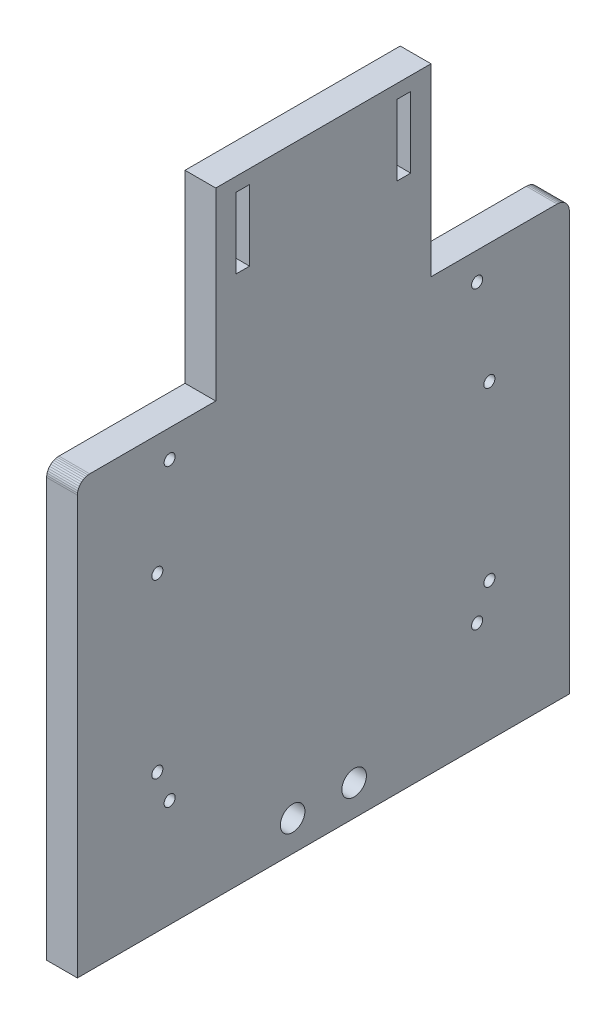
SolidWorks part; units mm, degrees
material "PLA"
ref_plane "Front Plane" through (0, 0, 0) normal (0, 0, 1) x (1, 0, 0)
ref_plane "Top Plane" through (0, 0, 0) normal (0, 1, 0) x (1, 0, 0)
ref_plane "Right Plane" through (0, 0, 0) normal (1, 0, 0) x (0, 0, -1)
ref_plane "Plane4" through (-115.1122, 0, 0) normal (-1, 0, 0) x (0, -1, 0)
sketch "Sketch1" plane through (-115.1122, 0, 0) normal (-1, 0, 0) x (0, -1, 0)
  line L0 (-142.5814, 52.5665) -> (-142.5814, 132.5665)
  line L1 (-142.5814, 132.5665) -> (-210.5815, 132.5665)
  line L2 (-210.5815, 132.5665) -> (-210.8661, 132.5461)
  line L3 (-210.8661, 132.5461) -> (-211.1449, 132.4855)
  line L4 (-211.1449, 132.4855) -> (-211.4123, 132.3858)
  line L5 (-211.4123, 132.3858) -> (-211.6627, 132.249)
  line L6 (-211.6627, 132.249) -> (-211.8912, 132.078)
  line L7 (-211.8912, 132.078) -> (-212.093, 131.8762)
  line L8 (-212.093, 131.8762) -> (-212.264, 131.6478)
  line L9 (-212.264, 131.6478) -> (-212.4007, 131.3973)
  line L10 (-212.4007, 131.3973) -> (-212.5004, 131.13)
  line L11 (-212.5004, 131.13) -> (-212.5611, 130.8511)
  line L12 (-212.5611, 130.8511) -> (-212.5815, 130.5665)
  line L13 (-212.5815, 130.5665) -> (-212.5815, 54.5665)
  line L14 (-212.5815, 54.5665) -> (-212.5611, 54.2819)
  line L15 (-212.5611, 54.2819) -> (-212.5004, 54.003)
  line L16 (-212.5004, 54.003) -> (-212.4007, 53.7357)
  line L17 (-212.4007, 53.7357) -> (-212.264, 53.4852)
  line L18 (-212.264, 53.4852) -> (-212.093, 53.2568)
  line L19 (-212.093, 53.2568) -> (-211.8912, 53.055)
  line L20 (-211.8912, 53.055) -> (-211.6627, 52.884)
  line L21 (-211.6627, 52.884) -> (-211.4123, 52.7472)
  line L22 (-211.4123, 52.7472) -> (-211.1449, 52.6475)
  line L23 (-211.1449, 52.6475) -> (-210.8661, 52.5869)
  line L24 (-210.8661, 52.5869) -> (-210.5815, 52.5665)
  line L25 (-210.5815, 52.5665) -> (-142.5814, 52.5665)
extrude "Boss-Extrude1" add sketch "Sketch1" against normal blind 5
sketch "Sketch2" plane through (-115.1122, 0, 0) normal (-1, 0, 0) x (0, 0, 1)
  line L44 (97.5665, 149.5814) -> (97.5665, 145.5815) construction
  circle A0 centre (97.5665, 147.5815) radius 2
extrude "Cut-Extrude1" cut sketch "Sketch2" against normal through all
sketch "Sketch3" plane through (-110.1122, 0, 0) normal (1, 0, 0) x (0, 0, -1)
  line L44 (-87.5665, 149.5814) -> (-87.5665, 145.5815) construction
  circle A0 centre (-87.5665, 147.5815) radius 2
extrude "Cut-Extrude2" cut sketch "Sketch3" against normal through all
sketch "Sketch4" plane through (-110.1122, 0, 0) normal (1, 0, 0) x (0, 0, -1)
  line L36 (-119.5665, 165.9815) -> (-119.5665, 164.1815) construction
  circle A0 centre (-119.5665, 165.0815) radius 0.9
extrude "Cut-Extrude3" cut sketch "Sketch4" against normal blind 3
sketch "Sketch5" plane through (-115.1122, 0, 0) normal (-1, 0, 0) x (0, 0, 1)
  line L36 (125.0665, 160.9815) -> (125.0665, 159.1815) construction
  circle A0 centre (125.0665, 160.0815) radius 0.9
extrude "Cut-Extrude4" cut sketch "Sketch5" against normal blind 3
sketch "Sketch6" plane through (-115.1122, 0, 0) normal (-1, 0, 0) x (0, 0, 1)
  line L36 (60.0665, 160.9815) -> (60.0665, 159.1815) construction
  circle A0 centre (60.0665, 160.0815) radius 0.9
extrude "Cut-Extrude5" cut sketch "Sketch6" against normal blind 3
sketch "Sketch7" plane through (-110.1122, 0, 0) normal (1, 0, 0) x (0, 0, -1)
  line L36 (-67.5665, 160.9815) -> (-67.5665, 159.1815) construction
  circle A0 centre (-67.5665, 160.0815) radius 0.9
extrude "Cut-Extrude6" cut sketch "Sketch7" against normal blind 3
sketch "Sketch8" plane through (-115.1122, 0, 0) normal (-1, 0, 0) x (0, 0, 1)
  line L36 (125.0665, 205.9815) -> (125.0665, 204.1815) construction
  circle A0 centre (125.0665, 205.0815) radius 0.9
extrude "Cut-Extrude7" cut sketch "Sketch8" against normal blind 3
sketch "Sketch9" plane through (-115.1122, 0, 0) normal (-1, 0, 0) x (0, 0, 1)
  line L36 (60.0665, 205.9815) -> (60.0665, 204.1815) construction
  circle A0 centre (60.0665, 205.0815) radius 0.9
extrude "Cut-Extrude8" cut sketch "Sketch9" against normal blind 3
sketch "Sketch10" plane through (-110.1122, 0, 0) normal (1, 0, 0) x (0, 0, -1)
  line L36 (-119.5665, 193.9815) -> (-119.5665, 192.1815) construction
  circle A0 centre (-119.5665, 193.0815) radius 0.9
extrude "Cut-Extrude9" cut sketch "Sketch10" against normal blind 3
sketch "Sketch11" plane through (-110.1122, 0, 0) normal (1, 0, 0) x (0, 0, -1)
  line L36 (-67.5665, 208.9815) -> (-67.5665, 207.1815) construction
  circle A0 centre (-67.5665, 208.0815) radius 0.9
extrude "Cut-Extrude10" cut sketch "Sketch11" against normal blind 3
sketch "Sketch12" plane through (-110.1122, 0, 0) normal (1, 0, 0) x (0, 0, -1)
  line L0 (-87.5665, 147.5815) -> (-97.5665, 147.5815) construction
  line L1 (-92.5665, 147.5815) -> (-92.5665, 234.5815) construction
  line L2 (-110.0665, 226.5815) -> (-110.0665, 212.5815)
  line L3 (-75.0665, 242.5815) -> (-110.0665, 242.5815)
  line L4 (-75.0665, 242.5815) -> (-75.0665, 226.5815)
  line L6 (-110.0665, 242.5815) -> (-110.0665, 226.5815)
  line L7 (-75.0665, 242.5815) -> (-110.0665, 226.5815) construction
  line L8 (-75.0665, 226.5815) -> (-110.0665, 242.5815) construction
  line L9 (-104.5665, 234.5815) -> (-80.5665, 234.5815) construction
  line L10 (-130.5665, 212.5815) -> (-54.5665, 212.5815) construction
  line L11 (-106.7665, 240.3315) -> (-104.5665, 240.3315)
  line L12 (-106.7665, 240.3315) -> (-106.7665, 228.8315)
  line L13 (-106.7665, 228.8315) -> (-104.5665, 228.8315)
  line L14 (-104.5665, 240.3315) -> (-104.5665, 228.8315)
  line L15 (-80.5665, 240.3315) -> (-78.3665, 240.3315)
  line L16 (-80.5665, 240.3315) -> (-80.5665, 228.8315)
  line L17 (-80.5665, 228.8315) -> (-78.3665, 228.8315)
  line L18 (-78.3665, 240.3315) -> (-78.3665, 228.8315)
  line L19 (-110.0665, 212.5815) -> (-75.0665, 212.5815)
  line L20 (-75.0665, 212.5815) -> (-75.0665, 226.5815)
  point P14 (-92.5665, 234.5815)
  point P19 (-104.5665, 234.5815)
  point P24 (-80.5665, 234.5815)
  dimension "D1" = 35
  dimension "D2" = 30
  dimension "D3" = 24
  dimension "D4" = 11.5
  dimension "D5" = 2.2
  dimension "D6" = 8
extrude "Boss-Extrude2" add sketch "Sketch12" against normal blind 5
sketch "Sketch13" plane through (-110.1122, 0, 0) normal (1, 0, 0) x (0, 0, -1)
  line L0 (-92.5665, 242.5815) -> (-92.5665, 142.5814) construction
  line L1 (-132.5665, 142.5814) -> (-132.5665, 210.5815) construction
  line L2 (-52.5665, 210.5815) -> (-52.5665, 142.5814) construction
  line L3 (-75.0665, 242.5815) -> (-110.0665, 242.5815) construction
  line L4 (-52.5665, 142.5814) -> (-132.5665, 142.5814) construction
ref_plane "Plane5" through (0, 0, 92.5665) normal (0, 0, 1) x (0, -1, 0)
mirror "Mirror1" about plane through (0, 0, 92.5665) normal (0, 0, 1) of "Cut-Extrude3", "Cut-Extrude6", "Cut-Extrude9", "Cut-Extrude10"
